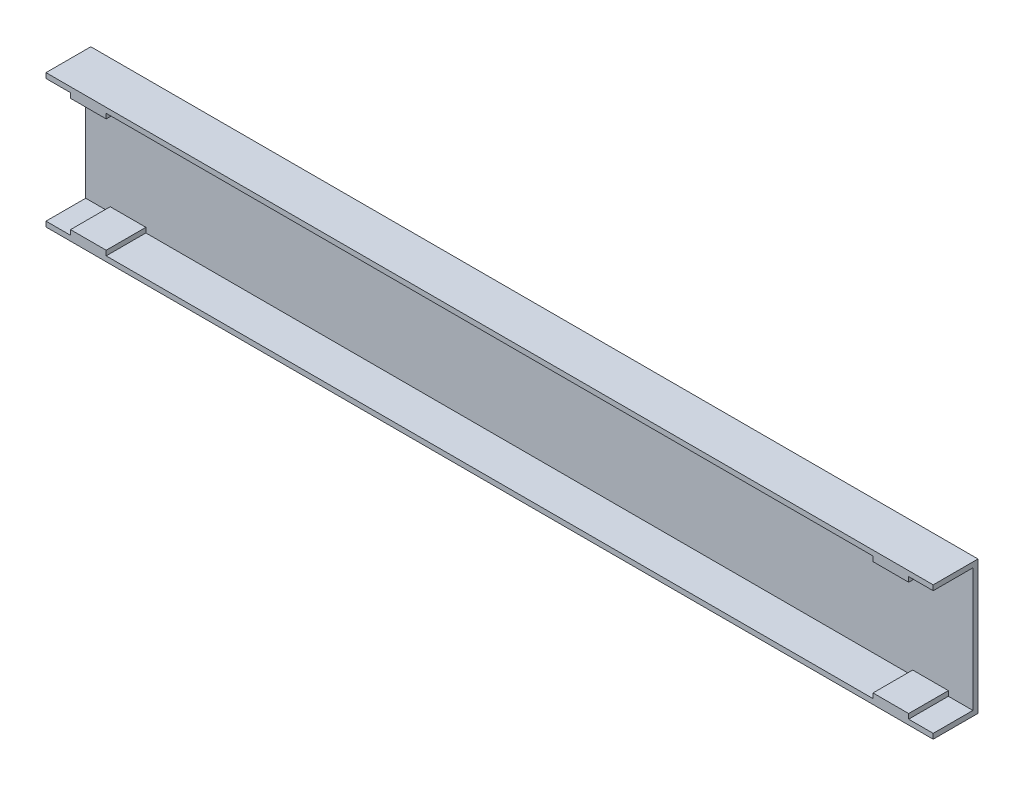
SolidWorks part; units mm, degrees
ref_plane "前视" through (0, 0, 0) normal (0, 0, 1) x (1, 0, 0)
ref_plane "上视" through (0, 0, 0) normal (0, 1, 0) x (1, 0, 0)
ref_plane "右视" through (0, 0, 0) normal (1, 0, 0) x (0, 0, -1)
sketch "草图1" plane through (0, 0, 0) normal (0, 0, 1) x (1, 0, 0)
  line L0 (0, 0) -> (0, 71.3124) construction
  line L2 (-995, 0) -> (995, 0)
  line L3 (-995, 0) -> (-995, 300)
  line L4 (-995, 300) -> (995, 300)
  line L5 (995, 0) -> (995, 300)
  line L6 (0, 188.8094) -> (0, 294.6471) construction
  line L7 (300, 294.6471) -> (300, -20.2744) construction
  line L8 (49.1838, 70) -> (952.4051, 70) construction
  line L9 (49.1838, 150) -> (1036.2895, 150) construction
  line L10 (49.1838, 230) -> (1036.2895, 230) construction
  dimension "D1" = 1990
  dimension "D2" = 300
  dimension "D4" = 70
  dimension "D5" = 80
  dimension "D6" = 80
extrude "基体-拉伸" add sketch "草图1" along normal blind 11.5
sketch "草图2" plane through (0, 0, 11.5) normal (0, 0, 1) x (1, 0, 0)
  line L0 (995, 0) -> (995, 300) construction
  line L1 (-995, 300) -> (995, 300)
  line L2 (-995, 300) -> (-995, 288.5)
  line L3 (-995, 288.5) -> (-940, 288.5)
  line L4 (995, 300) -> (995, 288.5)
  line L5 (472.8445, 150) -> (989.2832, 150) construction
  line L6 (-995, 0) -> (995, 0)
  line L7 (-995, 0) -> (-995, 11.5)
  line L8 (-995, 11.5) -> (-940, 11.5)
  line L9 (995, 0) -> (995, 11.5)
  line L10 (940, 288.5) -> (940, 277.5)
  line L11 (860, 11.5) -> (860, 22.5)
  line L12 (860, 22.5) -> (940, 22.5)
  line L13 (940, 11.5) -> (940, 22.5)
  line L14 (940, 11.5) -> (995, 11.5)
  line L15 (860, 288.5) -> (860, 277.5)
  line L16 (860, 277.5) -> (940, 277.5)
  line L17 (940, 288.5) -> (995, 288.5)
  line L18 (0, 0) -> (0, 280.097) construction
  line L19 (-940, 11.5) -> (-940, 22.5)
  line L20 (-860, 11.5) -> (-860, 22.5)
  line L21 (-860, 22.5) -> (-940, 22.5)
  line L22 (-940, 288.5) -> (-940, 277.5)
  line L23 (-860, 288.5) -> (-860, 277.5)
  line L24 (-860, 277.5) -> (-940, 277.5)
  line L25 (-860, 288.5) -> (860, 288.5)
  line L26 (-860, 11.5) -> (860, 11.5)
  dimension "D1" = 11.5
  dimension "D3" = 55
  dimension "D4" = 80
  dimension "D5" = 11
  dimension "D6" = 150
extrude "凸台-拉伸1" add sketch "草图2" along normal blind 89
sketch "草图7" plane through (0, 0, 0) normal (0, 0, -1) x (-1, 0, 0)
  line L0 (0, 0) -> (0, 358.9057) construction
  line L1 (265, 265) -> (335, 265)
  line L2 (265, 265) -> (265, 35)
  line L3 (265, 35) -> (335, 35)
  line L4 (335, 265) -> (335, 35)
  line L6 (995, 0) -> (-995, 0) construction
  line L7 (300, 333.2202) -> (300, -69.0551) construction
  line L8 (-335, 265) -> (-335, 35)
  line L9 (-265, 35) -> (-335, 35)
  line L10 (-265, 265) -> (-265, 35)
  line L11 (-265, 265) -> (-335, 265)
  circle A0 centre (300, 230) radius 13
  circle A1 centre (300, 150) radius 13
  circle A2 centre (300, 70) radius 13
  circle A3 centre (-300, 70) radius 13
  circle A4 centre (-300, 150) radius 13
  circle A5 centre (-300, 230) radius 13
  dimension "D6" = 26
  dimension "D1" = 265
  dimension "D2" = 70
  dimension "D3" = 230
  dimension "D4" = 35
  dimension "D5" = 35
  dimension "D7" = 70
  dimension "D8" = 80
  dimension "D9" = 80
extrude "凸台-拉伸2" add sketch "草图7" along normal blind 16
